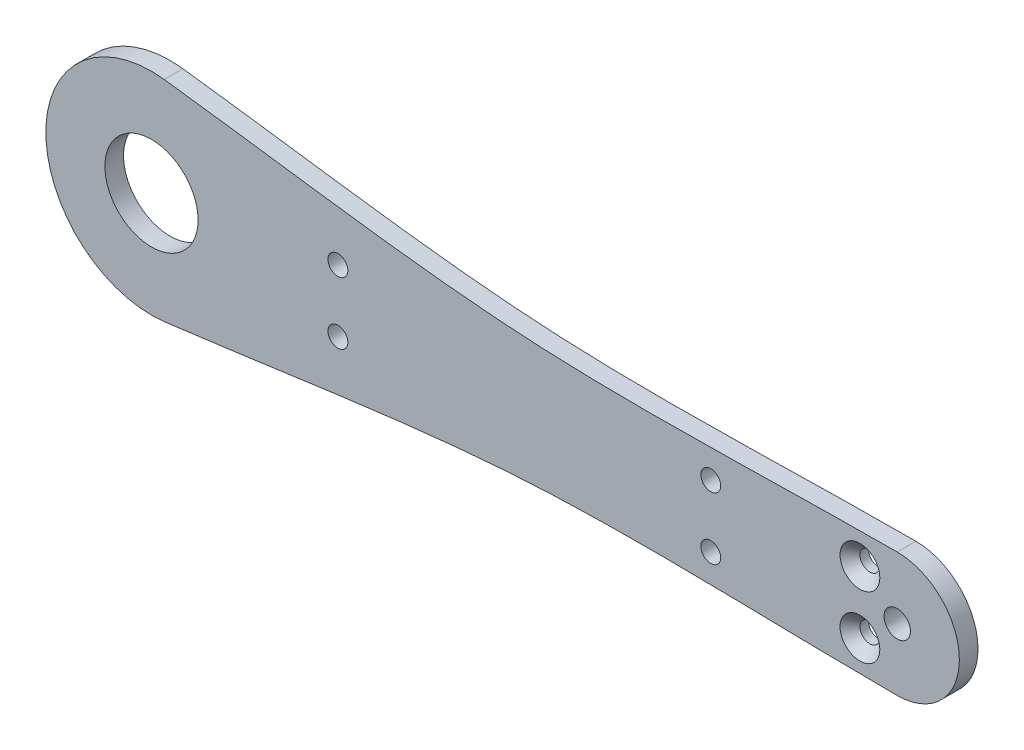
SolidWorks part; units mm, degrees
ref_plane "Front Plane" through (0, 0, 0) normal (0, 0, 1) x (1, 0, 0)
ref_plane "Top Plane" through (0, 0, 0) normal (0, 1, 0) x (1, 0, 0)
ref_plane "Right Plane" through (0, 0, 0) normal (1, 0, 0) x (0, 0, -1)
sketch "Sketch1" plane through (0, 0, 0) normal (0, 0, 1) x (1, 0, 0)
  line L0 (-103.1351, 0) -> (103.1351, 0) construction
  line L3 (0, 10) -> (0, -10) construction
  circle A2 centre (-60, 0) radius 7.5
  circle A3 centre (60, 0) radius 2.125
  arc A4 (-57.9568, 16.8768) -> (-57.9568, -16.8768) centre (-60, 0) ccw
  arc A5 (60, -10) -> (60, 10) centre (60, 0) ccw
  circle A6 centre (-30, 5) radius 1.6
  circle A7 centre (30, 5) radius 1.6
  circle A8 centre (30, -5) radius 1.6
  circle A9 centre (-30, -5) radius 1.6
  spline S0 degree 3 poles (60, 10) (39.9383, 10) (0.416, 7.6936) (-38.5985, 14.4869) (-57.9568, 16.8768) knots 0 0 0 0 0.506914 1 1 1 1
  spline S1 degree 3 poles (60, -10) (39.9383, -10) (0.416, -7.6936) (-38.5985, -14.4869) (-57.9568, -16.8768) knots 0 0 0 0 0.506914 1 1 1 1
  point P7 (0, 0)
  dimension "D3" = 15
  dimension "D1" = 4.25
  dimension "D2" = 34
  dimension "D4" = 20
  dimension "D10" = 3.2
  dimension "D5" = 120
  dimension "D6" = 20
  dimension "D7" = 60
  dimension "D8" = 30
  dimension "D9" = 5
  dimension "D14" = 30
  dimension "D15" = 5
  dimension "D12" = 2
  dimension "D13" = 2
extrude "Boss-Extrude1" add sketch "Sketch1" along normal blind 3
sketch "Sketch2" plane through (0, 0, 3) normal (0, 0, 1) x (1, 0, 0)
  line L0 (60, 0) -> (73.8031, 0) construction
  circle A0 centre (60, 0) radius 2.125 construction
  circle A1 centre (60, 0) radius 2.125 construction
  circle A4 centre (54, 5) radius 1.6
  circle A5 centre (54, -5) radius 1.6
  dimension "D3" = 3.2
  dimension "D1" = 6
  dimension "D2" = 5
extrude "Cut-Extrude1" cut sketch "Sketch2" against normal through all
chamfer "Chamfer1" distance 1.6 angle 45 2 edges at (52.4, -5, 3) (55.6, 5, 3)
equation "\"L1\"= 120mm'Upper arm"
equation "\"L3\"= 75mm'Wrist→TCP"
equation "\"h0\"= 75mm'Shoulder height"
equation "\"t_link\"= 3mm'Link plate thickness"
equation "\"t_bracket\"= 4mm'Bracket thickness"
equation "\"d_pin\"= 4mm'Pin diameter (M4)"
equation "\"c_fit\"= 0.2mm'Nominal clearance - measured PLA 2026-10-01"
equation "\"L2\"= 120mm'Forearm"
equation "\"c_fit_pivot\"= \"c_fit\" + 0.05mm'Gripper pivot clearance - chosen 0.25 mm 2026-10-01"
equation "\"d_pin_gripper\"= 3mm'Gripper pivot diameter"
equation "\"w_link\"= 20mm'Link plate depth (bending direction)"
equation "\"w_gap\"= 20mm'Twin-plate gap - provisional, set by elbow servo mount"
equation "\"D1@Boss-Extrude1\"=\"t_link\""
equation "\"d_boss\"= 13mm'MG996R output boss dia - from downloaded model, verify with calipers"
equation "\"c_boss\"= 1mm'Radial clearance around servo boss"
equation "\"d_servo_hole\"= \"d_boss\" + 2 * \"c_boss\"'Plate clearance hole for servo boss (15 mm)"
equation "\"t_rim\"= 9.5mm'Min material around servo hole (M3 hole + 3 mm webs each side)"
equation "\"w_link_end\"= \"d_servo_hole\" + 2 * \"t_rim\"'Link plate end width at servo end (34 mm)"
equation "\"d_hole_m3\"= \"d_pin_gripper\" + \"c_fit\"'M3 bolt clearance hole (spacer and adapter bolts)"
equation "\"d_hole_pivot\"= \"d_pin\" + \"c_fit_pivot\"'M4 pivot hole where the pin rotates (4.25 mm)"
equation "\"D3@Sketch1\"=\"d_servo_hole\""
equation "\"D1@Sketch1\"=\"d_pin\"+\"c_fit_pivot\""
equation "\"D2@Sketch1\"=\"w_link_end\""
equation "\"D4@Sketch1\"=\"w_link\""
equation "\"D5@Sketch1\"=\"L1\""
equation "\"D6@Sketch1\"=\"w_link\""
equation "\"D10@Sketch1\"=\"d_hole_m3\""
equation "\"d_horn\"= 20mm'Horn disc diameter (circular horn) - from MG996R model"
equation "\"t_horn\"= 2.3mm'Horn disc thickness"
equation "\"g_horn\"= 2.2mm'Gap from horn disc to plate 2 inner face - from MockShoulder"
equation "\"d_horn_pocket\"= \"d_horn\" + \"c_fit\"'Adapter pocket for horn disc (20.2 mm)"
equation "\"h_horn_pocket\"= \"g_horn\" + \"t_horn\"'Pocket depth from adapter plate-2 face (4.5 mm)"
equation "\"d_horn_screw_cb\"= 8.5mm'Recess for horn centre-screw head (head is 7.5 mm)"
equation "\"h_horn_screw_cb\"= 2.6mm'Recess depth (head is 2.35 mm tall)"
equation "\"d_adapter\"= 26mm'Horn adapter outer diameter"
equation "\"h_adapter\"= \"w_gap\"'Adapter length, fills the plate gap"
equation "\"t_adapter_floor\"= 2mm'Floor under horn disc that the horn screws pass through"
equation "\"d_horn_screw_hole\"= 2.2mm'Clearance for M2 self-tapper through the floor"
equation "\"r_horn_screw\"= 7mm'Horn screw hole radius (14 mm square pattern)"
equation "\"d_access\"= 4mm'Access bore for the M2 screws from the plate-1 side"
equation "\"d_insert_m3\"= 4mm'Hole for M3 heat-set insert - HZYUEGOU M3 inserts are 4.2 OD, hole 4.0; open to 4.1 if too tight"
equation "\"h_insert_m3\"= 6mm'Insert hole depth"
equation "\"x_adapter_bolt\"= 6mm'Adapter bolt offset from pin, along the arm toward its middle"
equation "\"y_adapter_bolt\"= 5mm'Adapter bolt offset from pin, across the arm (+/-)"
equation "\"d_csk_m3\"= 6.4mm'Countersink diameter in plate 1 for M3 flat head (90 deg)"
equation "\"h_pin_bore\"= 10mm'M4 pin engagement depth in the adapter"
equation "\"D1@Sketch2\"=\"x_adapter_bolt\""
equation "\"D2@Sketch2\"=\"y_adapter_bolt\""
equation "\"D3@Sketch2\"=\"d_hole_m3\""
equation "\"D1@Chamfer1\"=(\"d_csk_m3\" - \"d_hole_m3\") / 2"
